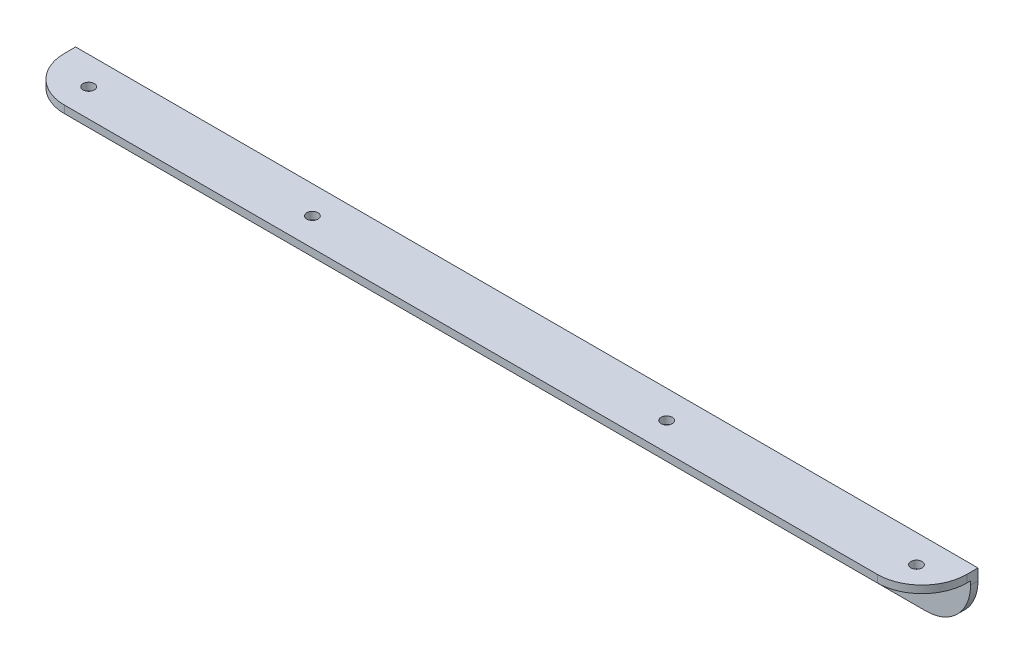
SolidWorks part; units mm, degrees
ref_plane "Front Plane" through (0, 0, 0) normal (0, 0, 1) x (1, 0, 0)
ref_plane "Top Plane" through (0, 0, 0) normal (0, 1, 0) x (1, 0, 0)
ref_plane "Right Plane" through (0, 0, 0) normal (1, 0, 0) x (0, 0, -1)
sketch "Sketch1" plane through (0, 0, 0) normal (0, 0, 1) x (1, 0, 0)
  line L0 (-121, 0) -> (121, 0)
  line L2 (55, 0) -> (-55, 0) construction
  line L3 (-121, 0) -> (-121, -13)
  line L4 (121, 0) -> (121, -13)
  line L5 (-121, -13) -> (121, -13)
  line L6 (-121, -6.5) -> (121, -6.5) construction
  circle A0 centre (-114, -6.5) radius 1.5
  circle A1 centre (-44, -6.5) radius 1.5
  circle A2 centre (-24, -6.5) radius 1.5
  circle A3 centre (27, -6.5) radius 1.5
  circle A4 centre (97, -6.5) radius 1.5
  point P4 (0, 0)
  point P11 (97, -6.5)
  point P12 (27, -6.5)
  point P13 (-24, -6.5)
  point P14 (-44, -6.5)
  point P15 (-114, -6.5)
  dimension "D1" = 242
  dimension "D2" = 24
  dimension "D3" = 70
  dimension "D4" = 51
  dimension "D5" = 20
  dimension "D6" = 70
extrude "Boss-Extrude1" add sketch "Sketch1" along normal blind 2
sketch "Sketch2" plane through (0, 0, 2) normal (0, 0, 1) x (1, 0, 0)
  line L0 (121, -13) -> (12, -13) construction
  line L1 (-121, -13) -> (121, -13) construction
  line L2 (12, -13) -> (12, -9)
  line L3 (12, -9) -> (-18, -9)
  line L4 (-18, -9) -> (-18, -13)
  line L5 (-18, -13) -> (12, -13)
  dimension "D1" = 4
  dimension "D2" = 30
extrude "Cut-Extrude1" cut sketch "Sketch2" against normal up to next
sketch "Sketch3" plane through (0, 0, 0) normal (0, 0, 1) x (1, 0, 0)
  line L0 (-121, 0) -> (121, 0)
  line L1 (-121, 0) -> (-121, 2)
  line L2 (121, 0) -> (121, 2)
  line L3 (-121, 2) -> (121, 2)
  dimension "D1" = 2
extrude "Boss-Extrude2" add sketch "Sketch3" along normal blind 15
sketch "Sketch4" plane through (0, 2, 0) normal (0, 1, 0) x (1, 0, 0)
  line L0 (-121, -7.5) -> (121, -7.5) construction
  line L1 (-121, -15) -> (-121, 0) construction
  line L2 (121, -15) -> (121, 0) construction
  circle A0 centre (-110, -7.5) radius 1.5
  circle A1 centre (-50, -7.5) radius 1.5
  circle A2 centre (45, -7.5) radius 1.5
  circle A3 centre (112, -7.5) radius 1.5
  point P6 (-110, -7.5)
  point P7 (-50, -7.5)
  point P8 (45, -7.5)
  point P9 (112, -7.5)
  dimension "D1" = 11
  dimension "D2" = 60
  dimension "D3" = 9
  dimension "D4" = 67
extrude "Cut-Extrude2" cut sketch "Sketch4" against normal up to next
fillet "Fillet1" radius 12 4 edges at (-121, -13, 1) (121, -13, 1) (121, 1, 15) (-121, 1, 15)
